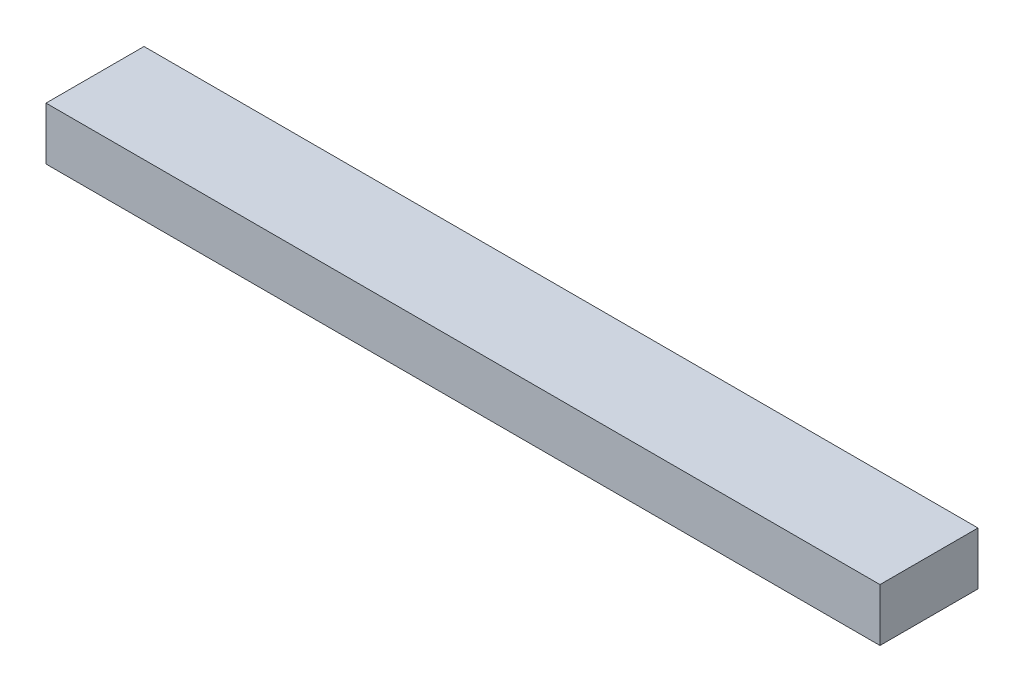
SolidWorks part; units mm, degrees
ref_plane "前视基准面" through (0, 0, 0) normal (0, 0, 1) x (1, 0, 0)
ref_plane "上视基准面" through (0, 0, 0) normal (0, 1, 0) x (1, 0, 0)
ref_plane "右视基准面" through (0, 0, 0) normal (1, 0, 0) x (0, 0, -1)
sketch "草图1" plane through (0, 0, 0) normal (0, 1, 0) x (1, 0, 0)
  line L1 (-53.683, 21.9906) -> (56.917, 21.9906)
  line L2 (-53.683, 21.9906) -> (-53.683, 8.9906)
  line L3 (-53.683, 8.9906) -> (56.917, 8.9906)
  line L4 (56.917, 21.9906) -> (56.917, 8.9906)
  circle A0 centre (-50.183, 15.9906) radius 1.5
  circle A1 centre (-11.683, 11.4906) radius 1.5
  circle A2 centre (54.8525, 11.4906) radius 1.5
  point P8 (1.2899, 11.1297)
  point P11 (54.8525, 11.4906)
  dimension "D3" = 3
  dimension "D1" = 110.6
  dimension "D2" = 13
  dimension "D4" = 3.5
  dimension "D5" = 6
  dimension "D6" = 42
  dimension "D7" = 2.5
extrude "凸台-拉伸1" add sketch "草图1" along normal blind 7 contours L1 L4 L3 L2
